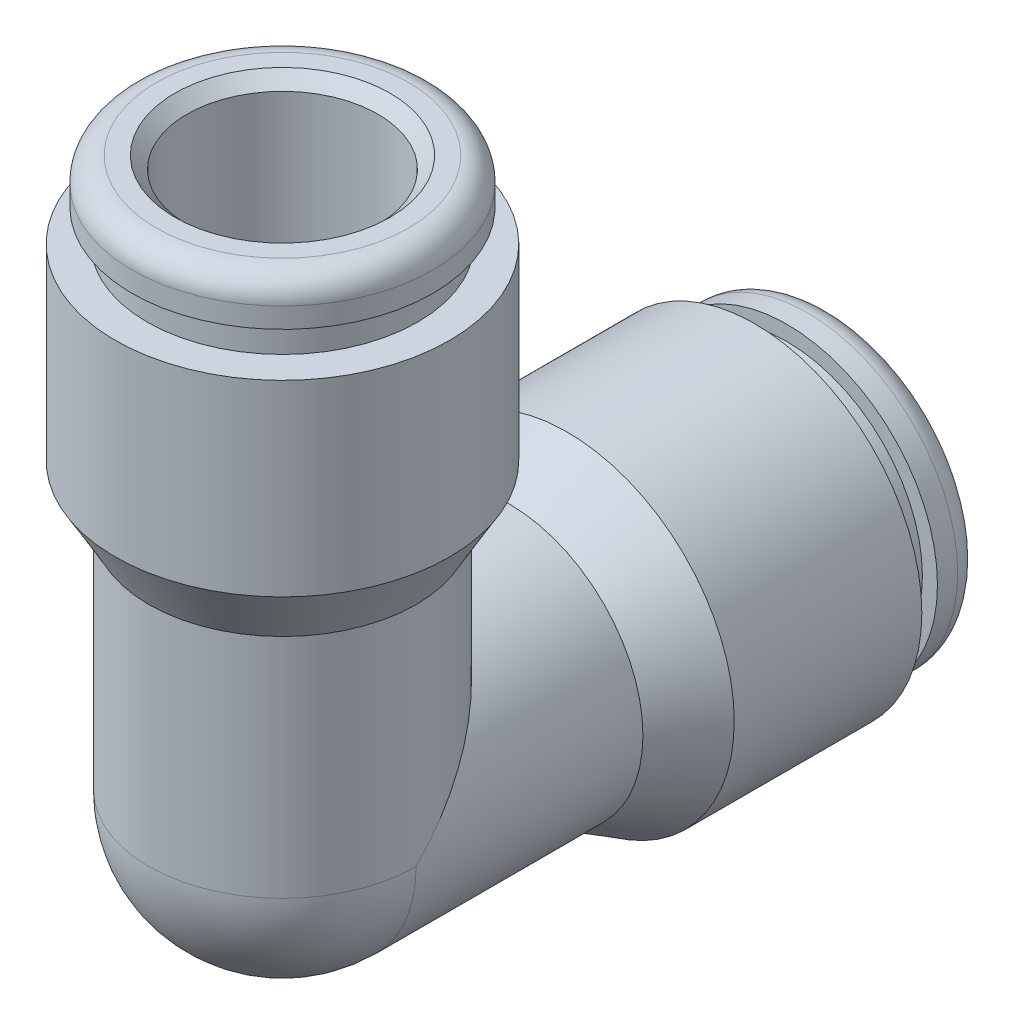
SolidWorks part; units mm, degrees
ref_plane "Front Plane" through (0, 0, 0) normal (0, 0, 1) x (1, 0, 0)
ref_plane "Top Plane" through (0, 0, 0) normal (0, 1, 0) x (1, 0, 0)
ref_plane "Right Plane" through (0, 0, 0) normal (1, 0, 0) x (0, 0, -1)
sketch "Sketch1" plane through (0, 0, 0) normal (1, 0, 0) x (0, 0, -1)
  line L0 (15.853, 4.725) -> (16.488, 4.725)
  line L1 (8.9437, 5.25) -> (14.837, 5.25)
  line L2 (0, 4.2) -> (0, 2.238)
  line L3 (6, 3) -> (16.869, 3)
  line L4 (17.25, 3.963) -> (17.25, 3.381)
  line L5 (0, 0) -> (0, 17.25) construction
  line L6 (14.837, 5.25) -> (14.837, 4.2525)
  line L7 (14.837, 4.2525) -> (15.853, 4.2525)
  line L8 (15.853, 4.725) -> (15.853, 4.2525)
  line L9 (-5.25, 17.25) -> (5.25, 17.25) construction
  line L10 (0, 0) -> (17.25, 0) construction
  line L11 (6, 3) -> (6, 2.238)
  line L12 (16.869, 3) -> (17.25, 3.381)
  line L13 (0, 0) -> (0, 2.238) construction
  line L14 (0, 4.2) -> (7.125, 4.2)
  line L15 (7.125, 4.2) -> (8.9437, 5.25)
  line L16 (6, 2.238) -> (0, 2.238)
  arc A0 (16.488, 4.725) -> (17.25, 3.963) centre (16.488, 3.963) cw
  point P1 (17.25, 3)
  point P20 (17.25, 4.725)
  dimension "D4" = 0.762
  dimension "tube od" = 6
  dimension "D1" = 1.397
  dimension "D2" = 1.016
  dimension "D3" = 8.505
  dimension "D6" = 9.45
  dimension "D9" = 30
  dimension "D10" = 8.4
  dimension "D5" = 10.125
  dimension "D8" = 10.5
  dimension "D11" = 0.762
revolve "Revolve1" add sketch "Sketch1" angle 360 about L10
ref_axis "Axis1" through (-5.775, 0, 0) along (1, 0, 0)
pattern_circular "CirPattern1" count 2 over 90 about axis through (-5.775, 0, 0) along (1, 0, 0) of bodies 118 123
sketch "Sketch2" plane through (0, 0, 0) normal (0, 0, 1) x (1, 0, 0)
  line L0 (-4.2, 0) -> (-2.238, 0)
  line L1 (-4.2, 0) -> (4.2, 0) construction
  line L2 (2.238, 0) -> (4.2, 0)
  arc A0 (-4.2, 0) -> (4.2, 0) centre (0, 0) ccw
  arc A2 (-2.238, 0) -> (2.238, 0) centre (0, 0) ccw
  circle A4 centre (0, 0) radius 2.238 construction
  circle A5 centre (0, 0) radius 4.2 construction
revolve "Revolve2" add sketch "Sketch2" angle 90 about L1
combine bodies "Combine1" operation type add bodies to combine 122 124
sketch "Sketch3" plane through (0, 0, 0) normal (1, 0, 0) x (0, 0, -1)
  line L0 (17.25, 3.381) -> (16.869, 3)
  line L1 (16.869, 3) -> (6, 3)
  line L2 (6, 3) -> (6, 2.238)
  line L3 (6, 2.238) -> (0, 2.238)
  line L4 (0, 2.238) -> (0, 0)
  line L5 (0, 0) -> (17.25, 0)
  line L6 (17.25, 0) -> (17.25, 3.381)
revolve "Cut-Revolve1" cut sketch "Sketch3" angle 360 about L5
pattern_circular "CirPattern2" count 2 over 90 about axis through (-5.775, 0, 0) along (1, 0, 0) of "Cut-Revolve1"
equation "\"D6@Sketch1\" = \"G@Sketch1\"*.9"
equation "\"D3@Sketch1\" = \"D6@Sketch1\"*.9"
equation "\"D10@Sketch1\" = \"G@Sketch1\"*.8"
equation "\"D5@Sketch1\" = \"L@Sketch1\"*.45"
equation "\"D8@Sketch1\" = \"G@Sketch1\""
